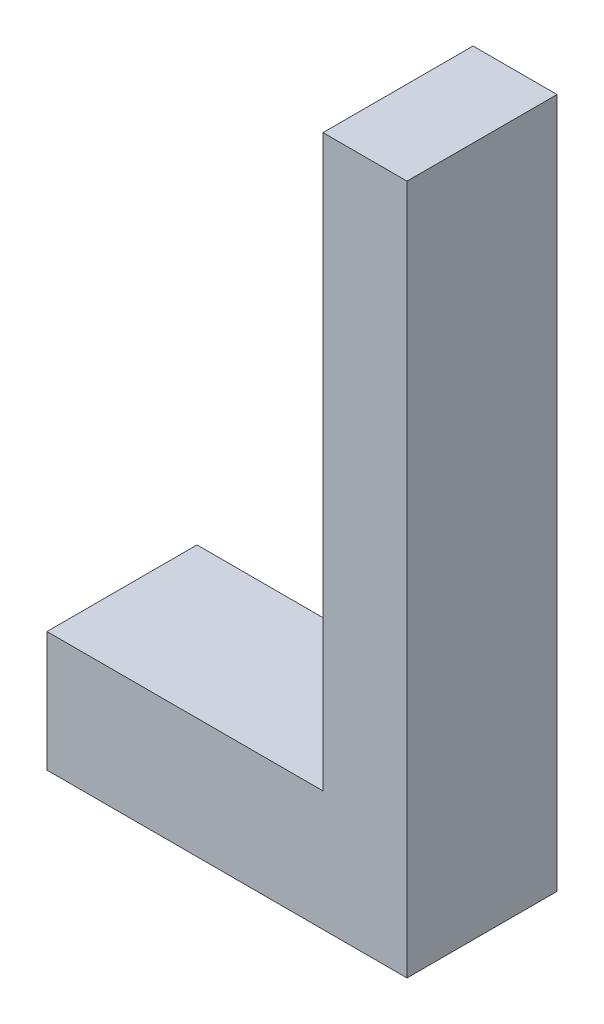
SolidWorks part; units mm, degrees
ref_plane "Front Plane" through (0, 0, 0) normal (0, 0, 1) x (1, 0, 0)
ref_plane "Top Plane" through (0, 0, 0) normal (0, 1, 0) x (1, 0, 0)
ref_plane "Right Plane" through (0, 0, 0) normal (1, 0, 0) x (0, 0, -1)
sketch "Sketch1" plane through (0, 0, 0) normal (0, 0, 1) x (1, 0, 0)
  line L0 (0, 0) -> (0, 1)
  line L1 (0, 1) -> (3, 1)
  line L2 (0, 0) -> (3, 0)
  line L3 (3, 0) -> (3, 1)
  dimension "D1" = 1
  dimension "D2" = 3
extrude "Boss-Extrude1" add sketch "Sketch1" along normal blind 1.25
sketch "Sketch3" plane through (0, 0, 1.25) normal (0, 0, 1) x (1, 0, 0)
  line L3 (3, 0) -> (3, 1)
  line L8 (3, 1) -> (3, 5.75)
  line L9 (4.7125, 5.75) -> (-32.7323, 5.75) construction
  line L10 (3, 5.75) -> (2.2998, 5.75)
  line L11 (2.2998, 5.75) -> (2.2998, 1)
  line L12 (3, 1) -> (0, 1) construction
  line L13 (2.2998, 1) -> (3, 1)
  line M7 (3, 1) -> (0, 1)
extrude "Boss-Extrude2" add sketch "Sketch3" against normal up to surface (1.25 mm away) contours L10 L11 L8 M7 up to face at (1.5, 0.5, 0)
